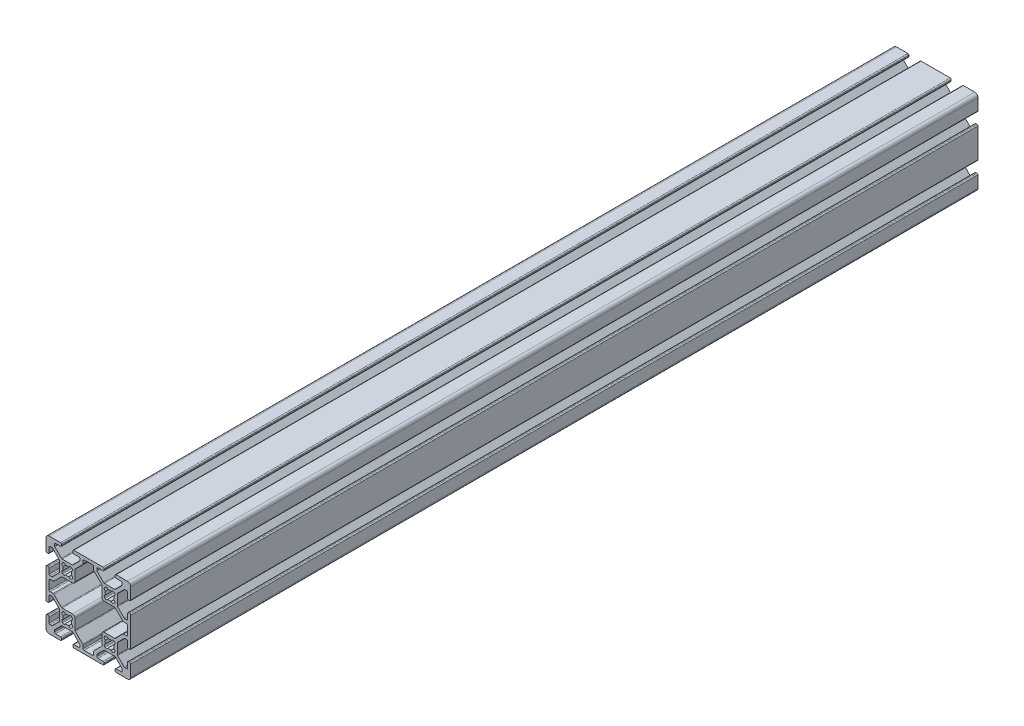
SolidWorks part; units mm, degrees
material "6061 Alloy"
ref_plane "Front Plane" through (0, 0, 0) normal (0, 0, 1) x (1, 0, 0)
ref_plane "Top Plane" through (0, 0, 0) normal (0, 1, 0) x (1, 0, 0)
ref_plane "Right Plane" through (0, 0, 0) normal (1, 0, 0) x (0, 0, -1)
sketch "Sketch1" plane through (0, 0, 0) normal (0, 0, 1) x (1, 0, 0)
  line L0 (-16.6492, -131.4291) -> (-16.8288, -131.2495)
  line L1 (-16.8288, -126.9997) -> (-16.6492, -126.8201)
  line L2 (-12.3994, -126.8201) -> (-12.2198, -126.9997)
  line L3 (-12.2198, -131.2495) -> (-12.3994, -131.4291)
  line L4 (-36.6492, -131.4291) -> (-36.8288, -131.2495)
  line L5 (-36.8288, -126.9997) -> (-36.6492, -126.8201)
  line L6 (-32.3994, -126.8201) -> (-32.2198, -126.9997)
  line L7 (-32.2198, -131.2495) -> (-32.3994, -131.4291)
  line L8 (-16.6492, -151.4291) -> (-16.8288, -151.2495)
  line L9 (-16.8288, -146.9997) -> (-16.6492, -146.8201)
  line L10 (-12.3994, -146.8201) -> (-12.2198, -146.9997)
  line L11 (-12.2198, -151.2495) -> (-12.3994, -151.4291)
  line L12 (-27.0293, -157.1166) -> (-27.0293, -155.7694)
  line L13 (-27.1781, -155.4102) -> (-30.7205, -151.8677)
  line L14 (-30.8693, -151.5085) -> (-30.8693, -146.6126)
  line L15 (-32.0123, -145.4696) -> (-36.9082, -145.4696)
  line L16 (-37.2674, -145.3208) -> (-40.8098, -141.7784)
  line L17 (-41.169, -141.6296) -> (-42.5163, -141.6296)
  line L18 (-43.0243, -141.1216) -> (-43.0243, -137.1276)
  line L19 (-42.5163, -136.6196) -> (-41.169, -136.6196)
  line L20 (-40.8098, -136.4708) -> (-37.2674, -132.9284)
  line L21 (-36.9082, -132.7796) -> (-32.0123, -132.7796)
  line L22 (-30.8693, -131.6366) -> (-30.8693, -126.7407)
  line L23 (-30.7205, -126.3815) -> (-27.1781, -122.8391)
  line L24 (-27.0293, -122.4798) -> (-27.0293, -121.1326)
  line L25 (-26.5213, -120.6246) -> (-22.5273, -120.6246)
  line L26 (-22.0193, -121.1326) -> (-22.0193, -122.4798)
  line L27 (-21.8705, -122.8391) -> (-18.3281, -126.3815)
  line L28 (-18.1793, -126.7407) -> (-18.1793, -131.6366)
  line L29 (-17.0363, -132.7796) -> (-12.1404, -132.7796)
  line L30 (-11.7812, -132.9284) -> (-8.2387, -136.4708)
  line L31 (-7.8795, -136.6196) -> (-6.5323, -136.6196)
  line L32 (-6.0243, -137.1276) -> (-6.0243, -141.1216)
  line L33 (-6.5323, -141.6296) -> (-7.8795, -141.6296)
  line L34 (-8.2387, -141.7784) -> (-11.7812, -145.3208)
  line L35 (-12.1404, -145.4696) -> (-17.0363, -145.4696)
  line L36 (-18.1793, -146.6126) -> (-18.1793, -151.5085)
  line L37 (-18.3281, -151.8677) -> (-21.8705, -155.4102)
  line L38 (-22.0193, -155.7694) -> (-22.0193, -157.1166)
  line L39 (-22.5273, -157.6246) -> (-26.5213, -157.6246)
  line L40 (-36.6492, -151.4291) -> (-36.8288, -151.2495)
  line L41 (-36.8288, -146.9997) -> (-36.6492, -146.8201)
  line L42 (-32.3994, -146.8201) -> (-32.2198, -146.9997)
  line L43 (-32.2198, -151.2495) -> (-32.3994, -151.4291)
  line L44 (-36.9082, -152.7796) -> (-32.1404, -152.7796)
  line L45 (-31.7812, -152.9284) -> (-28.6781, -156.0315)
  line L46 (-28.5293, -156.3907) -> (-28.5293, -157.1166)
  line L47 (-29.0373, -157.6246) -> (-31.3863, -157.6246)
  line L48 (-31.8943, -158.1326) -> (-31.8943, -158.6166)
  line L49 (-31.3863, -159.1246) -> (-17.6623, -159.1246)
  line L50 (-17.1543, -158.6166) -> (-17.1543, -158.1326)
  line L51 (-17.6623, -157.6246) -> (-20.0113, -157.6246)
  line L52 (-20.5193, -157.1166) -> (-20.5193, -156.3907)
  line L53 (-20.3705, -156.0315) -> (-17.2674, -152.9284)
  line L54 (-16.9082, -152.7796) -> (-12.1404, -152.7796)
  line L55 (-11.7812, -152.9284) -> (-8.6781, -156.0315)
  line L56 (-8.5293, -156.3907) -> (-8.5293, -157.1166)
  line L57 (-9.0373, -157.6246) -> (-11.3863, -157.6246)
  line L58 (-11.8943, -158.1326) -> (-11.8943, -158.6166)
  line L59 (-11.3863, -159.1246) -> (-6.0243, -159.1246)
  line L60 (-4.5243, -157.6246) -> (-4.5243, -152.2626)
  line L61 (-5.0323, -151.7546) -> (-5.5163, -151.7546)
  line L62 (-6.0243, -152.2626) -> (-6.0243, -154.6116)
  line L63 (-6.5323, -155.1196) -> (-7.2582, -155.1196)
  line L64 (-7.6174, -154.9708) -> (-10.7205, -151.8677)
  line L65 (-10.8693, -151.5085) -> (-10.8693, -146.7407)
  line L66 (-10.7205, -146.3815) -> (-7.6174, -143.2784)
  line L67 (-7.2582, -143.1296) -> (-6.5323, -143.1296)
  line L68 (-6.0243, -143.6376) -> (-6.0243, -145.9866)
  line L69 (-5.5163, -146.4946) -> (-5.0323, -146.4946)
  line L70 (-4.5243, -145.9866) -> (-4.5243, -132.2626)
  line L71 (-5.0323, -131.7546) -> (-5.5163, -131.7546)
  line L72 (-6.0243, -132.2626) -> (-6.0243, -134.6116)
  line L73 (-6.5323, -135.1196) -> (-7.2582, -135.1196)
  line L74 (-7.6174, -134.9708) -> (-10.7205, -131.8677)
  line L75 (-10.8693, -131.5085) -> (-10.8693, -126.7407)
  line L76 (-10.7205, -126.3815) -> (-7.6174, -123.2784)
  line L77 (-7.2582, -123.1296) -> (-6.5323, -123.1296)
  line L78 (-6.0243, -123.6376) -> (-6.0243, -125.9866)
  line L79 (-5.5163, -126.4946) -> (-5.0323, -126.4946)
  line L80 (-4.5243, -125.9866) -> (-4.5243, -120.6246)
  line L81 (-6.0243, -119.1246) -> (-11.3863, -119.1246)
  line L82 (-11.8943, -119.6326) -> (-11.8943, -120.1166)
  line L83 (-11.3863, -120.6246) -> (-9.0373, -120.6246)
  line L84 (-8.5293, -121.1326) -> (-8.5293, -121.8585)
  line L85 (-8.6781, -122.2177) -> (-11.7812, -125.3208)
  line L86 (-12.1404, -125.4696) -> (-16.9082, -125.4696)
  line L87 (-17.2674, -125.3208) -> (-20.3705, -122.2177)
  line L88 (-20.5193, -121.8585) -> (-20.5193, -121.1326)
  line L89 (-20.0113, -120.6246) -> (-17.6623, -120.6246)
  line L90 (-17.1543, -120.1166) -> (-17.1543, -119.6326)
  line L91 (-17.6623, -119.1246) -> (-31.3863, -119.1246)
  line L92 (-31.8943, -119.6326) -> (-31.8943, -120.1166)
  line L93 (-31.3863, -120.6246) -> (-29.0373, -120.6246)
  line L94 (-28.5293, -121.1326) -> (-28.5293, -121.8585)
  line L95 (-28.6781, -122.2177) -> (-31.7812, -125.3208)
  line L96 (-32.1404, -125.4696) -> (-36.9082, -125.4696)
  line L97 (-37.2674, -125.3208) -> (-40.3705, -122.2177)
  line L98 (-40.5193, -121.8585) -> (-40.5193, -121.1326)
  line L99 (-40.0113, -120.6246) -> (-37.6623, -120.6246)
  line L100 (-37.1543, -120.1166) -> (-37.1543, -119.6326)
  line L101 (-37.6623, -119.1246) -> (-43.0243, -119.1246)
  line L102 (-44.5243, -120.6246) -> (-44.5243, -125.9866)
  line L103 (-44.0163, -126.4946) -> (-43.5323, -126.4946)
  line L104 (-43.0243, -125.9866) -> (-43.0243, -123.6376)
  line L105 (-42.5163, -123.1296) -> (-41.7904, -123.1296)
  line L106 (-41.4312, -123.2784) -> (-38.3281, -126.3815)
  line L107 (-38.1793, -126.7407) -> (-38.1793, -131.5085)
  line L108 (-38.3281, -131.8677) -> (-41.4312, -134.9708)
  line L109 (-41.7904, -135.1196) -> (-42.5163, -135.1196)
  line L110 (-43.0243, -134.6116) -> (-43.0243, -132.2626)
  line L111 (-43.5323, -131.7546) -> (-44.0163, -131.7546)
  line L112 (-44.5243, -132.2626) -> (-44.5243, -145.9866)
  line L113 (-44.0163, -146.4946) -> (-43.5323, -146.4946)
  line L114 (-43.0243, -145.9866) -> (-43.0243, -143.6376)
  line L115 (-42.5163, -143.1296) -> (-41.7904, -143.1296)
  line L116 (-41.4312, -143.2784) -> (-38.3281, -146.3815)
  line L117 (-38.1793, -146.7407) -> (-38.1793, -151.5085)
  line L118 (-38.3281, -151.8677) -> (-41.4312, -154.9708)
  line L119 (-41.7904, -155.1196) -> (-42.5163, -155.1196)
  line L120 (-43.0243, -154.6116) -> (-43.0243, -152.2626)
  line L121 (-43.5323, -151.7546) -> (-44.0163, -151.7546)
  line L122 (-44.5243, -152.2626) -> (-44.5243, -157.6246)
  line L123 (-43.0243, -159.1246) -> (-37.6623, -159.1246)
  line L124 (-37.1543, -158.6166) -> (-37.1543, -158.1326)
  line L125 (-37.6623, -157.6246) -> (-40.0113, -157.6246)
  line L126 (-40.5193, -157.1166) -> (-40.5193, -156.3907)
  line L127 (-40.3705, -156.0315) -> (-37.2674, -152.9284)
  arc A0 (-16.4594, -129.9286) -> (-16.8288, -131.2495) centre (-16.2723, -130.693) ccw
  arc A1 (-16.4594, -128.3206) -> (-16.4594, -129.9286) centre (-14.5243, -129.1246) ccw
  arc A2 (-16.8288, -126.9997) -> (-16.4594, -128.3206) centre (-16.2723, -127.5562) ccw
  arc A3 (-15.3283, -127.1895) -> (-16.6492, -126.8201) centre (-16.0927, -127.3766) ccw
  arc A4 (-13.7203, -127.1895) -> (-15.3283, -127.1895) centre (-14.5243, -129.1246) ccw
  arc A5 (-12.3994, -126.8201) -> (-13.7203, -127.1895) centre (-12.9559, -127.3766) ccw
  arc A6 (-12.5892, -128.3206) -> (-12.2198, -126.9997) centre (-12.7763, -127.5562) ccw
  arc A7 (-12.5892, -129.9286) -> (-12.5892, -128.3206) centre (-14.5243, -129.1246) ccw
  arc A8 (-12.2198, -131.2495) -> (-12.5892, -129.9286) centre (-12.7763, -130.693) ccw
  arc A9 (-13.7203, -131.0597) -> (-12.3994, -131.4291) centre (-12.9559, -130.8726) ccw
  arc A10 (-15.3283, -131.0597) -> (-13.7203, -131.0597) centre (-14.5243, -129.1246) ccw
  arc A11 (-16.6492, -131.4291) -> (-15.3283, -131.0597) centre (-16.0927, -130.8726) ccw
  arc A12 (-36.4594, -129.9286) -> (-36.8288, -131.2495) centre (-36.2723, -130.693) ccw
  arc A13 (-36.4594, -128.3206) -> (-36.4594, -129.9286) centre (-34.5243, -129.1246) ccw
  arc A14 (-36.8288, -126.9997) -> (-36.4594, -128.3206) centre (-36.2723, -127.5562) ccw
  arc A15 (-35.3283, -127.1895) -> (-36.6492, -126.8201) centre (-36.0927, -127.3766) ccw
  arc A16 (-33.7203, -127.1895) -> (-35.3283, -127.1895) centre (-34.5243, -129.1246) ccw
  arc A17 (-32.3994, -126.8201) -> (-33.7203, -127.1895) centre (-32.9559, -127.3766) ccw
  arc A18 (-32.5892, -128.3206) -> (-32.2198, -126.9997) centre (-32.7763, -127.5562) ccw
  arc A19 (-32.5892, -129.9286) -> (-32.5892, -128.3206) centre (-34.5243, -129.1246) ccw
  arc A20 (-32.2198, -131.2495) -> (-32.5892, -129.9286) centre (-32.7763, -130.693) ccw
  arc A21 (-33.7203, -131.0597) -> (-32.3994, -131.4291) centre (-32.9559, -130.8726) ccw
  arc A22 (-35.3283, -131.0597) -> (-33.7203, -131.0597) centre (-34.5243, -129.1246) ccw
  arc A23 (-36.6492, -131.4291) -> (-35.3283, -131.0597) centre (-36.0927, -130.8726) ccw
  arc A24 (-16.4594, -149.9286) -> (-16.8288, -151.2495) centre (-16.2723, -150.693) ccw
  arc A25 (-16.4594, -148.3206) -> (-16.4594, -149.9286) centre (-14.5243, -149.1246) ccw
  arc A26 (-16.8288, -146.9997) -> (-16.4594, -148.3206) centre (-16.2723, -147.5562) ccw
  arc A27 (-15.3283, -147.1895) -> (-16.6492, -146.8201) centre (-16.0927, -147.3766) ccw
  arc A28 (-13.7203, -147.1895) -> (-15.3283, -147.1895) centre (-14.5243, -149.1246) ccw
  arc A29 (-12.3994, -146.8201) -> (-13.7203, -147.1895) centre (-12.9559, -147.3766) ccw
  arc A30 (-12.5892, -148.3206) -> (-12.2198, -146.9997) centre (-12.7763, -147.5562) ccw
  arc A31 (-12.5892, -149.9286) -> (-12.5892, -148.3206) centre (-14.5243, -149.1246) ccw
  arc A32 (-12.2198, -151.2495) -> (-12.5892, -149.9286) centre (-12.7763, -150.693) ccw
  arc A33 (-13.7203, -151.0597) -> (-12.3994, -151.4291) centre (-12.9559, -150.8726) ccw
  arc A34 (-15.3283, -151.0597) -> (-13.7203, -151.0597) centre (-14.5243, -149.1246) ccw
  arc A35 (-16.6492, -151.4291) -> (-15.3283, -151.0597) centre (-16.0927, -150.8726) ccw
  arc A36 (-27.0293, -157.1166) -> (-26.5213, -157.6246) centre (-26.5213, -157.1166) ccw
  arc A37 (-27.0293, -155.7694) -> (-27.1781, -155.4102) centre (-27.5373, -155.7694) ccw
  arc A38 (-30.8693, -151.5085) -> (-30.7205, -151.8677) centre (-30.3613, -151.5085) ccw
  arc A39 (-30.8693, -146.6126) -> (-32.0123, -145.4696) centre (-32.0123, -146.6126) ccw
  arc A40 (-37.2674, -145.3208) -> (-36.9082, -145.4696) centre (-36.9082, -144.9616) ccw
  arc A41 (-40.8098, -141.7784) -> (-41.169, -141.6296) centre (-41.169, -142.1376) ccw
  arc A42 (-43.0243, -141.1216) -> (-42.5163, -141.6296) centre (-42.5163, -141.1216) ccw
  arc A43 (-42.5163, -136.6196) -> (-43.0243, -137.1276) centre (-42.5163, -137.1276) ccw
  arc A44 (-41.169, -136.6196) -> (-40.8098, -136.4708) centre (-41.169, -136.1116) ccw
  arc A45 (-36.9082, -132.7796) -> (-37.2674, -132.9284) centre (-36.9082, -133.2876) ccw
  arc A46 (-32.0123, -132.7796) -> (-30.8693, -131.6366) centre (-32.0123, -131.6366) ccw
  arc A47 (-30.7205, -126.3815) -> (-30.8693, -126.7407) centre (-30.3613, -126.7407) ccw
  arc A48 (-27.1781, -122.8391) -> (-27.0293, -122.4798) centre (-27.5373, -122.4798) ccw
  arc A49 (-26.5213, -120.6246) -> (-27.0293, -121.1326) centre (-26.5213, -121.1326) ccw
  arc A50 (-22.0193, -121.1326) -> (-22.5273, -120.6246) centre (-22.5273, -121.1326) ccw
  arc A51 (-22.0193, -122.4798) -> (-21.8705, -122.8391) centre (-21.5113, -122.4798) ccw
  arc A52 (-18.1793, -126.7407) -> (-18.3281, -126.3815) centre (-18.6873, -126.7407) ccw
  arc A53 (-18.1793, -131.6366) -> (-17.0363, -132.7796) centre (-17.0363, -131.6366) ccw
  arc A54 (-11.7812, -132.9284) -> (-12.1404, -132.7796) centre (-12.1404, -133.2876) ccw
  arc A55 (-8.2387, -136.4708) -> (-7.8795, -136.6196) centre (-7.8795, -136.1116) ccw
  arc A56 (-6.0243, -137.1276) -> (-6.5323, -136.6196) centre (-6.5323, -137.1276) ccw
  arc A57 (-6.5323, -141.6296) -> (-6.0243, -141.1216) centre (-6.5323, -141.1216) ccw
  arc A58 (-7.8795, -141.6296) -> (-8.2387, -141.7784) centre (-7.8795, -142.1376) ccw
  arc A59 (-12.1404, -145.4696) -> (-11.7812, -145.3208) centre (-12.1404, -144.9616) ccw
  arc A60 (-17.0363, -145.4696) -> (-18.1793, -146.6126) centre (-17.0363, -146.6126) ccw
  arc A61 (-18.3281, -151.8677) -> (-18.1793, -151.5085) centre (-18.6873, -151.5085) ccw
  arc A62 (-21.8705, -155.4102) -> (-22.0193, -155.7694) centre (-21.5113, -155.7694) ccw
  arc A63 (-22.5273, -157.6246) -> (-22.0193, -157.1166) centre (-22.5273, -157.1166) ccw
  arc A64 (-36.4594, -149.9286) -> (-36.8288, -151.2495) centre (-36.2723, -150.693) ccw
  arc A65 (-36.4594, -148.3206) -> (-36.4594, -149.9286) centre (-34.5243, -149.1246) ccw
  arc A66 (-36.8288, -146.9997) -> (-36.4594, -148.3206) centre (-36.2723, -147.5562) ccw
  arc A67 (-35.3283, -147.1895) -> (-36.6492, -146.8201) centre (-36.0927, -147.3766) ccw
  arc A68 (-33.7203, -147.1895) -> (-35.3283, -147.1895) centre (-34.5243, -149.1246) ccw
  arc A69 (-32.3994, -146.8201) -> (-33.7203, -147.1895) centre (-32.9559, -147.3766) ccw
  arc A70 (-32.5892, -148.3206) -> (-32.2198, -146.9997) centre (-32.7763, -147.5562) ccw
  arc A71 (-32.5892, -149.9286) -> (-32.5892, -148.3206) centre (-34.5243, -149.1246) ccw
  arc A72 (-32.2198, -151.2495) -> (-32.5892, -149.9286) centre (-32.7763, -150.693) ccw
  arc A73 (-33.7203, -151.0597) -> (-32.3994, -151.4291) centre (-32.9559, -150.8726) ccw
  arc A74 (-35.3283, -151.0597) -> (-33.7203, -151.0597) centre (-34.5243, -149.1246) ccw
  arc A75 (-36.6492, -151.4291) -> (-35.3283, -151.0597) centre (-36.0927, -150.8726) ccw
  arc A76 (-36.9082, -152.7796) -> (-37.2674, -152.9284) centre (-36.9082, -153.2876) ccw
  arc A77 (-31.7812, -152.9284) -> (-32.1404, -152.7796) centre (-32.1404, -153.2876) ccw
  arc A78 (-28.5293, -156.3907) -> (-28.6781, -156.0315) centre (-29.0373, -156.3907) ccw
  arc A79 (-29.0373, -157.6246) -> (-28.5293, -157.1166) centre (-29.0373, -157.1166) ccw
  arc A80 (-31.3863, -157.6246) -> (-31.8943, -158.1326) centre (-31.3863, -158.1326) ccw
  arc A81 (-31.8943, -158.6166) -> (-31.3863, -159.1246) centre (-31.3863, -158.6166) ccw
  arc A82 (-17.6623, -159.1246) -> (-17.1543, -158.6166) centre (-17.6623, -158.6166) ccw
  arc A83 (-17.1543, -158.1326) -> (-17.6623, -157.6246) centre (-17.6623, -158.1326) ccw
  arc A84 (-20.5193, -157.1166) -> (-20.0113, -157.6246) centre (-20.0113, -157.1166) ccw
  arc A85 (-20.3705, -156.0315) -> (-20.5193, -156.3907) centre (-20.0113, -156.3907) ccw
  arc A86 (-16.9082, -152.7796) -> (-17.2674, -152.9284) centre (-16.9082, -153.2876) ccw
  arc A87 (-11.7812, -152.9284) -> (-12.1404, -152.7796) centre (-12.1404, -153.2876) ccw
  arc A88 (-8.5293, -156.3907) -> (-8.6781, -156.0315) centre (-9.0373, -156.3907) ccw
  arc A89 (-9.0373, -157.6246) -> (-8.5293, -157.1166) centre (-9.0373, -157.1166) ccw
  arc A90 (-11.3863, -157.6246) -> (-11.8943, -158.1326) centre (-11.3863, -158.1326) ccw
  arc A91 (-11.8943, -158.6166) -> (-11.3863, -159.1246) centre (-11.3863, -158.6166) ccw
  arc A92 (-6.0243, -159.1246) -> (-4.5243, -157.6246) centre (-6.0243, -157.6246) ccw
  arc A93 (-4.5243, -152.2626) -> (-5.0323, -151.7546) centre (-5.0323, -152.2626) ccw
  arc A94 (-5.5163, -151.7546) -> (-6.0243, -152.2626) centre (-5.5163, -152.2626) ccw
  arc A95 (-6.5323, -155.1196) -> (-6.0243, -154.6116) centre (-6.5323, -154.6116) ccw
  arc A96 (-7.6174, -154.9708) -> (-7.2582, -155.1196) centre (-7.2582, -154.6116) ccw
  arc A97 (-10.8693, -151.5085) -> (-10.7205, -151.8677) centre (-10.3613, -151.5085) ccw
  arc A98 (-10.7205, -146.3815) -> (-10.8693, -146.7407) centre (-10.3613, -146.7407) ccw
  arc A99 (-7.2582, -143.1296) -> (-7.6174, -143.2784) centre (-7.2582, -143.6376) ccw
  arc A100 (-6.0243, -143.6376) -> (-6.5323, -143.1296) centre (-6.5323, -143.6376) ccw
  arc A101 (-6.0243, -145.9866) -> (-5.5163, -146.4946) centre (-5.5163, -145.9866) ccw
  arc A102 (-5.0323, -146.4946) -> (-4.5243, -145.9866) centre (-5.0323, -145.9866) ccw
  arc A103 (-4.5243, -132.2626) -> (-5.0323, -131.7546) centre (-5.0323, -132.2626) ccw
  arc A104 (-5.5163, -131.7546) -> (-6.0243, -132.2626) centre (-5.5163, -132.2626) ccw
  arc A105 (-6.5323, -135.1196) -> (-6.0243, -134.6116) centre (-6.5323, -134.6116) ccw
  arc A106 (-7.6174, -134.9708) -> (-7.2582, -135.1196) centre (-7.2582, -134.6116) ccw
  arc A107 (-10.8693, -131.5085) -> (-10.7205, -131.8677) centre (-10.3613, -131.5085) ccw
  arc A108 (-10.7205, -126.3815) -> (-10.8693, -126.7407) centre (-10.3613, -126.7407) ccw
  arc A109 (-7.2582, -123.1296) -> (-7.6174, -123.2784) centre (-7.2582, -123.6376) ccw
  arc A110 (-6.0243, -123.6376) -> (-6.5323, -123.1296) centre (-6.5323, -123.6376) ccw
  arc A111 (-6.0243, -125.9866) -> (-5.5163, -126.4946) centre (-5.5163, -125.9866) ccw
  arc A112 (-5.0323, -126.4946) -> (-4.5243, -125.9866) centre (-5.0323, -125.9866) ccw
  arc A113 (-4.5243, -120.6246) -> (-6.0243, -119.1246) centre (-6.0243, -120.6246) ccw
  arc A114 (-11.3863, -119.1246) -> (-11.8943, -119.6326) centre (-11.3863, -119.6326) ccw
  arc A115 (-11.8943, -120.1166) -> (-11.3863, -120.6246) centre (-11.3863, -120.1166) ccw
  arc A116 (-8.5293, -121.1326) -> (-9.0373, -120.6246) centre (-9.0373, -121.1326) ccw
  arc A117 (-8.6781, -122.2177) -> (-8.5293, -121.8585) centre (-9.0373, -121.8585) ccw
  arc A118 (-12.1404, -125.4696) -> (-11.7812, -125.3208) centre (-12.1404, -124.9616) ccw
  arc A119 (-17.2674, -125.3208) -> (-16.9082, -125.4696) centre (-16.9082, -124.9616) ccw
  arc A120 (-20.5193, -121.8585) -> (-20.3705, -122.2177) centre (-20.0113, -121.8585) ccw
  arc A121 (-20.0113, -120.6246) -> (-20.5193, -121.1326) centre (-20.0113, -121.1326) ccw
  arc A122 (-17.6623, -120.6246) -> (-17.1543, -120.1166) centre (-17.6623, -120.1166) ccw
  arc A123 (-17.1543, -119.6326) -> (-17.6623, -119.1246) centre (-17.6623, -119.6326) ccw
  arc A124 (-31.3863, -119.1246) -> (-31.8943, -119.6326) centre (-31.3863, -119.6326) ccw
  arc A125 (-31.8943, -120.1166) -> (-31.3863, -120.6246) centre (-31.3863, -120.1166) ccw
  arc A126 (-28.5293, -121.1326) -> (-29.0373, -120.6246) centre (-29.0373, -121.1326) ccw
  arc A127 (-28.6781, -122.2177) -> (-28.5293, -121.8585) centre (-29.0373, -121.8585) ccw
  arc A128 (-32.1404, -125.4696) -> (-31.7812, -125.3208) centre (-32.1404, -124.9616) ccw
  arc A129 (-37.2674, -125.3208) -> (-36.9082, -125.4696) centre (-36.9082, -124.9616) ccw
  arc A130 (-40.5193, -121.8585) -> (-40.3705, -122.2177) centre (-40.0113, -121.8585) ccw
  arc A131 (-40.0113, -120.6246) -> (-40.5193, -121.1326) centre (-40.0113, -121.1326) ccw
  arc A132 (-37.6623, -120.6246) -> (-37.1543, -120.1166) centre (-37.6623, -120.1166) ccw
  arc A133 (-37.1543, -119.6326) -> (-37.6623, -119.1246) centre (-37.6623, -119.6326) ccw
  arc A134 (-43.0243, -119.1246) -> (-44.5243, -120.6246) centre (-43.0243, -120.6246) ccw
  arc A135 (-44.5243, -125.9866) -> (-44.0163, -126.4946) centre (-44.0163, -125.9866) ccw
  arc A136 (-43.5323, -126.4946) -> (-43.0243, -125.9866) centre (-43.5323, -125.9866) ccw
  arc A137 (-42.5163, -123.1296) -> (-43.0243, -123.6376) centre (-42.5163, -123.6376) ccw
  arc A138 (-41.4312, -123.2784) -> (-41.7904, -123.1296) centre (-41.7904, -123.6376) ccw
  arc A139 (-38.1793, -126.7407) -> (-38.3281, -126.3815) centre (-38.6873, -126.7407) ccw
  arc A140 (-38.3281, -131.8677) -> (-38.1793, -131.5085) centre (-38.6873, -131.5085) ccw
  arc A141 (-41.7904, -135.1196) -> (-41.4312, -134.9708) centre (-41.7904, -134.6116) ccw
  arc A142 (-43.0243, -134.6116) -> (-42.5163, -135.1196) centre (-42.5163, -134.6116) ccw
  arc A143 (-43.0243, -132.2626) -> (-43.5323, -131.7546) centre (-43.5323, -132.2626) ccw
  arc A144 (-44.0163, -131.7546) -> (-44.5243, -132.2626) centre (-44.0163, -132.2626) ccw
  arc A145 (-44.5243, -145.9866) -> (-44.0163, -146.4946) centre (-44.0163, -145.9866) ccw
  arc A146 (-43.5323, -146.4946) -> (-43.0243, -145.9866) centre (-43.5323, -145.9866) ccw
  arc A147 (-42.5163, -143.1296) -> (-43.0243, -143.6376) centre (-42.5163, -143.6376) ccw
  arc A148 (-41.4312, -143.2784) -> (-41.7904, -143.1296) centre (-41.7904, -143.6376) ccw
  arc A149 (-38.1793, -146.7407) -> (-38.3281, -146.3815) centre (-38.6873, -146.7407) ccw
  arc A150 (-38.3281, -151.8677) -> (-38.1793, -151.5085) centre (-38.6873, -151.5085) ccw
  arc A151 (-41.7904, -155.1196) -> (-41.4312, -154.9708) centre (-41.7904, -154.6116) ccw
  arc A152 (-43.0243, -154.6116) -> (-42.5163, -155.1196) centre (-42.5163, -154.6116) ccw
  arc A153 (-43.0243, -152.2626) -> (-43.5323, -151.7546) centre (-43.5323, -152.2626) ccw
  arc A154 (-44.0163, -151.7546) -> (-44.5243, -152.2626) centre (-44.0163, -152.2626) ccw
  arc A155 (-44.5243, -157.6246) -> (-43.0243, -159.1246) centre (-43.0243, -157.6246) ccw
  arc A156 (-37.6623, -159.1246) -> (-37.1543, -158.6166) centre (-37.6623, -158.6166) ccw
  arc A157 (-37.1543, -158.1326) -> (-37.6623, -157.6246) centre (-37.6623, -158.1326) ccw
  arc A158 (-40.5193, -157.1166) -> (-40.0113, -157.6246) centre (-40.0113, -157.1166) ccw
  arc A159 (-40.3705, -156.0315) -> (-40.5193, -156.3907) centre (-40.0113, -156.3907) ccw
extrude "Extrude1" add sketch "Sketch1" along normal blind 400
